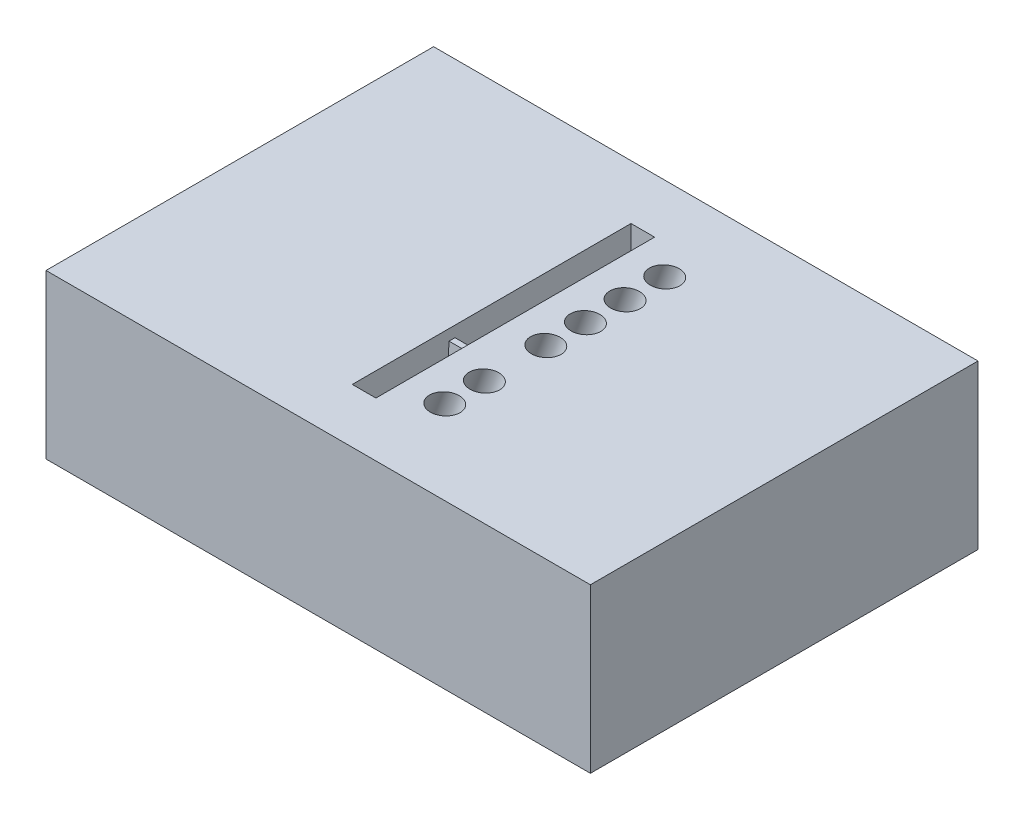
SolidWorks part; units mm, degrees
ref_plane "Front Plane" through (0, 0, 0) normal (0, 0, 1) x (1, 0, 0)
ref_plane "Top Plane" through (0, 0, 0) normal (0, 1, 0) x (1, 0, 0)
ref_plane "Right Plane" through (0, 0, 0) normal (1, 0, 0) x (0, 0, -1)
sketch "Sketch4" plane through (0, 0, 0) normal (0, 0, 1) x (1, 0, 0)
  line L0 (-1.2123, -11.7459) -> (1.5239, -4.2284)
  line L1 (-1.87, 0) -> (0.3, 0)
  line L2 (0, 0) -> (0, -10) construction
  line L3 (0, -10) -> (-1.57, -10) construction
  line L4 (-1.57, -10) -> (-1.57, 0) construction
  line L5 (-1.57, 0) -> (0, 0) construction
  line L6 (0.3, 0) -> (0.3, -10.3)
  line L7 (0.3, -10.3) -> (-1.87, -10.3)
  line L8 (-1.87, -10.3) -> (-1.87, 0)
  line L9 (-0.785, 0) -> (-0.785, -10.3) construction
  line L10 (-1.57, -10) -> (-1.87, -10) construction
  line L11 (-1.57, -10) -> (-1.57, -10.3) construction
  line L12 (3.9249, 0) -> (-0.4511, -12.023) construction
  line L13 (2.5202, 0) -> (5.3296, 0)
  line L14 (-1.2123, -11.7459) -> (0.31, -12.3)
  line L15 (0.31, -12.3) -> (3.0462, -4.7825)
  line L16 (3.0462, -4.7825) -> (3.5254, -4.9569)
  line L17 (3.5254, -4.9569) -> (5.3296, 0)
  line L18 (1.5239, -4.2284) -> (1.0446, -4.054)
  line L19 (1.0446, -4.054) -> (2.5202, 0)
  line L20 (0, -10) -> (0, -9)
  line L21 (1.5239, -4.2284) -> (3.0462, -4.7825) construction
  line L22 (1.7118, -4.2968) -> (-1.0243, -11.8143) construction
  line L23 (2.8583, -4.7141) -> (0.1221, -12.2316) construction
  line L24 (3.2435, -4.8543) -> (5.0103, 0) construction
  line L25 (0.31, -12.3) -> (-1.87, -12.3) construction
  line L26 (-1.87, -12.3) -> (-1.87, -10.3) construction
  dimension "D1" = 1.57
  dimension "D2" = 10
  dimension "D3" = 0.3
  dimension "D4" = 20
  dimension "D5" = 1
  dimension "D6" = 1.22
  dimension "D7" = 0.2
  dimension "D8" = 0.41
  dimension "D9" = 0.3
  dimension "D10" = 2
  dimension "D11" = 8
sketch "Sketch5" plane through (0, 0, 0) normal (0, 1, 0) x (1, 0, 0)
  line L0 (3.9249, 0) -> (3.9249, -3.9249) construction
  line L1 (3.9249, 0) -> (0, 0) construction
ref_plane "wireplane" through (3.4658, -1.2614, 0) normal (0.9397, -0.342, 0) x (0, 0, -1)
sketch "Sketch6" plane through (3.4658, -1.2614, 0) normal (0.9397, -0.342, 0) x (0, 0, -1)
  line L0 (0, -11.4522) -> (0, -3.4522) construction
  line L1 (0, 1.3424) -> (0, -11.4522) construction
  line L2 (0, -3.4522) -> (-8, -3.4522) construction
ref_plane "wiresectionplane" through (-1.1807, -3.244, 0) normal (-0.342, -0.9397, 0) x (-0.9397, 0.342, 0)
sketch "Sketch7" plane through (-1.1807, -3.244, 0) normal (-0.342, -0.9397, 0) x (-0.9397, 0.342, 0)
  line L0 (-2.3682, 0) -> (-5.0082, 0) construction
  line L1 (-2.3682, -11.42) -> (-2.3682, 11.42) construction
  line L2 (-2.3682, 11.42) -> (-5.0082, 11.42) construction
  line L3 (-5.0082, 11.42) -> (-5.0082, -11.42) construction
  line L4 (-5.0082, -11.42) -> (-2.3682, -11.42) construction
  line L5 (-2.8782, 11.42) -> (-2.8782, -11.42) construction
  line L6 (-4.4982, -11.42) -> (-4.4982, 11.42) construction
  line L7 (-3.6882, -11.42) -> (-3.6882, 11.42) construction
  line L8 (-3.6882, -8.78) -> (-6.3282, -8.78) construction
  line L9 (-6.3282, -8.78) -> (-6.3282, -7.78) construction
  line L10 (-6.3282, -7.78) -> (-3.6882, -7.78) construction
  line L11 (-3.6882, 8.78) -> (-6.3282, 8.78) construction
  line L12 (-6.3282, 8.78) -> (-6.3282, 7.78) construction
  line L13 (-6.3282, 7.78) -> (-3.6882, 7.78) construction
  line L14 (-3.6882, 5.14) -> (-6.3282, 5.14) construction
  line L15 (-6.3282, 5.14) -> (-6.3282, 4.14) construction
  line L16 (-6.3282, 4.14) -> (-3.6882, 4.14) construction
  line L17 (-3.6882, -5.14) -> (-1.0482, -5.14) construction
  line L18 (-1.0482, -5.14) -> (-1.0482, -2.14) construction
  line L19 (-1.0482, -2.14) -> (-3.6882, -2.14) construction
  line L20 (-3.6882, 1.5) -> (-6.3282, 1.5) construction
  line L21 (-6.3282, 1.5) -> (-6.3282, 0.5) construction
  line L22 (-6.3282, 0.5) -> (-3.6882, 0.5) construction
  circle A0 centre (-3.6882, 10.1) radius 1.32
  circle A1 centre (-3.6882, 6.46) radius 1.32
  circle A2 centre (-3.6882, 2.82) radius 1.32
  circle A3 centre (-3.6882, -0.82) radius 1.32
  circle A4 centre (-3.6882, -6.46) radius 1.32
  circle A5 centre (-3.6882, -10.1) radius 1.32
  dimension "D1" = 3
  dimension "D2" = 1
  dimension "D3" = 22.84
sketch "Sketch1" plane through (0, 0, 0) normal (0, 1, 0) x (1, 0, 0)
  line L0 (0, 0) -> (0, -17.8) construction
  line L1 (0, 0) -> (-25, 0) construction
  line L2 (-25, -11.42) -> (25, -11.42) construction
  line L3 (25, -17.8) -> (-25, -17.8)
  line L4 (25, -17.8) -> (25, 17.8)
  line L5 (25, 17.8) -> (-25, 17.8)
  line L6 (-25, -17.8) -> (-25, 17.8)
  line L7 (-0.785, 12.5) -> (-0.785, -12.5) construction
  line L8 (-1.87, 12.8) -> (0.3, 12.8) construction
  line L9 (-1.87, 12.8) -> (-1.87, -12.8) construction
  line L10 (-1.87, -12.8) -> (0.3, -12.8) construction
  line L11 (0.3, 12.8) -> (0.3, -12.8) construction
  line L12 (-1.57, 12.5) -> (0, 12.5) construction
  line L13 (-1.57, 12.5) -> (-1.57, -12.5) construction
  line L14 (-1.57, -12.5) -> (0, -12.5) construction
  line L15 (0, 12.5) -> (0, -12.5) construction
  line L16 (-1.57, -12.5) -> (-1.87, -12.5) construction
  line L17 (-1.57, -12.5) -> (-1.57, -12.8) construction
  dimension "D1" = 25
  dimension "D2" = 1.08
  dimension "D3" = 5
  dimension "D4" = 50
sketch "Sketch2" plane through (0, 0, 0) normal (1, 0, 0) x (0, 0, -1)
  line L0 (0, 0) -> (0, -15) construction
  line L1 (-17.8, 0) -> (17.8, 0)
  line L2 (-17.8, 0) -> (-17.8, -15)
  line L3 (-17.8, -15) -> (17.8, -15)
  line L4 (17.8, 0) -> (17.8, -15)
  dimension "D1" = 15
extrude "Boss-Extrude2" add sketch "Sketch1" against normal up to vertex (15 mm away) up to point (0, -15, 17.8)
sketch "Sketch9" plane through (0, 0, 0) normal (0, 1, 0) x (1, 0, 0)
  line L1 (-1.87, 12.8) -> (0.3, 12.8)
  line L2 (-1.87, 12.8) -> (-1.87, -12.8)
  line L3 (-1.87, -12.8) -> (0.3, -12.8)
  line L4 (0.3, 12.8) -> (0.3, -12.8)
extrude "Cut-Extrude1" cut sketch "Sketch9" against normal up to vertex (10.3 mm away) up to point (-1.87, -10.3, 0)
sketch "Sketch10" plane through (-1.1807, -3.244, 0) normal (-0.342, -0.9397, 0) x (-0.9397, 0.342, 0)
  line L0 (-2.8782, 11.42) -> (-2.8782, -11.42) construction
  line L1 (-4.4982, -11.42) -> (-4.4982, 11.42) construction
  line L2 (-2.8782, 11.42) -> (-2.8782, -11.42) construction
  line L3 (-4.4982, -11.42) -> (-4.4982, 11.42) construction
  circle A0 centre (-3.6882, -10.1) radius 0.81
  circle A1 centre (-3.6882, -6.46) radius 0.81
  circle A2 centre (-3.6882, -0.82) radius 0.81
  circle A3 centre (-3.6882, 2.82) radius 0.81
  circle A4 centre (-3.6882, 6.46) radius 0.81
  circle A5 centre (-3.6882, 10.1) radius 0.81
extrude "Cut-Extrude2" cut sketch "Sketch7" against normal through all
extrude "Cut-Extrude3" cut sketch "Sketch10" along normal up to vertex (8 mm away) up to point (-0.4511, -12.023, 0)
sketch "Sketch11" plane through (0, 0, 0) normal (1, 0, 0) x (0, 0, -1)
  line L0 (-3.64, -1) -> (-3.64, -10.3) construction
  line L1 (-3.64, -10) -> (-3.64, 0) construction
  line L2 (-4.4004, -10.3) -> (-2.8796, -10.3)
  line L3 (-3.913, -1) -> (-3.367, -1)
  line L4 (-3.367, -1) -> (-2.8796, -10.3)
  line L5 (-4.4004, -10.3) -> (-3.913, -1)
  line L6 (-4.3846, -10) -> (-3.913, -1) construction
extrude "Boss-Extrude3" add sketch "Sketch11" along normal up to vertex (0.3 mm away) and the other way up to vertex (1.87 mm away) up to point (0.3, -10.3, 0) other way up to point (-1.87, -10.3, 0)
